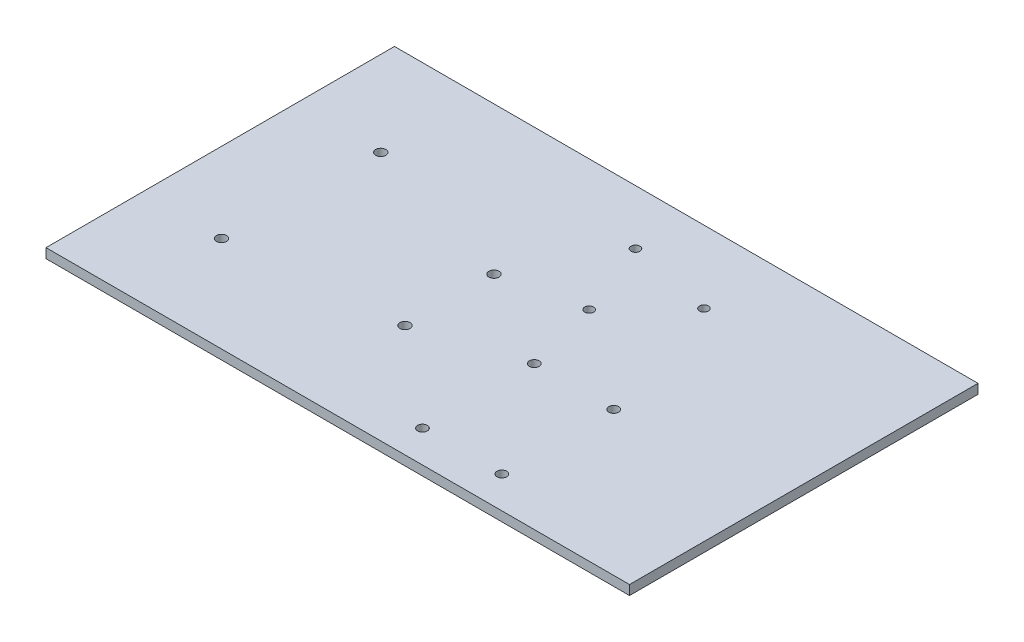
SolidWorks part; units mm, degrees
ref_plane "Front Plane" through (0, 0, 0) normal (0, 0, 1) x (1, 0, 0)
ref_plane "Top Plane" through (0, 0, 0) normal (0, 1, 0) x (1, 0, 0)
ref_plane "Right Plane" through (0, 0, 0) normal (1, 0, 0) x (0, 0, -1)
sketch "Sketch1" plane through (0, 0, 0) normal (0, 1, 0) x (1, 0, 0)
  line L1 (-91.44, 54.61) -> (91.44, 54.61)
  line L2 (-91.44, 54.61) -> (-91.44, -54.61)
  line L3 (-91.44, -54.61) -> (91.44, -54.61)
  line L4 (91.44, 54.61) -> (91.44, -54.61)
  line L5 (-91.44, 54.61) -> (91.44, -54.61) construction
  line L6 (-91.44, -54.61) -> (91.44, 54.61) construction
  point P0 (0, 0)
  dimension "D1" = 182.88
  dimension "D2" = 109.22
extrude "Boss-Extrude1" add sketch "Sketch1" along normal blind 3
sketch "Sketch2" plane through (0, 3, 0) normal (0, 1, 0) x (1, 0, 0)
  line L0 (-91.44, 54.61) -> (-91.44, -54.61) construction
  line L1 (-91.44, -54.61) -> (91.44, -54.61) construction
  line L2 (-66.44, -24.61) -> (-66.44, 28.3) construction
  line L3 (-66.44, -24.61) -> (52.1033, -24.61) construction
  circle A0 centre (-66.44, -24.61) radius 1.6
  circle A1 centre (-64.84, 23.69) radius 1.6
  circle A2 centre (-14.04, 8.39) radius 1.6
  circle A3 centre (-14.04, -19.51) radius 1.6
  dimension "D2" = 30
  dimension "D4" = 3.2
  dimension "D5" = 50.8
  dimension "D6" = 27.9
  dimension "D7" = 5.1
  dimension "D3" = 48.3
  dimension "D1" = 25
extrude "Cut-Extrude1" cut sketch "Sketch2" against normal blind 10
sketch "Sketch3" plane through (0, 3, 0) normal (0, 1, 0) x (1, 0, 0)
  line L0 (91.44, 54.61) -> (-91.44, 54.61) construction
  line L1 (91.44, -54.61) -> (91.44, 54.61) construction
  circle A0 centre (10.4954, 13.69) radius 1.4
  circle A1 centre (1.2336, 37.47) radius 1.4
  circle A2 centre (28.18, 31.98) radius 1.4
  dimension "D1" = 2.8
  dimension "D2" = 40.92
  dimension "D3" = 27.5
  dimension "D4" = 25.52
  dimension "D5" = 22.63
  dimension "D6" = 17.14
  dimension "D7" = 63.26
extrude "Cut-Extrude2" cut sketch "Sketch3" against normal through all
sketch "Sketch4" plane through (0, 3, 0) normal (0, 1, 0) x (1, 0, 0)
  line L0 (16.55, -9.56) -> (41.44, -9.56) construction
  line L1 (16.55, -9.56) -> (16.55, -44.61) construction
  line L2 (41.44, -9.56) -> (41.44, -44.61) construction
  line L3 (91.44, 54.61) -> (-91.44, 54.61) construction
  line L4 (91.44, -54.61) -> (91.44, 54.61) construction
  line L5 (-91.44, -54.61) -> (91.44, -54.61) construction
  circle A0 centre (16.55, -44.61) radius 1.525
  circle A1 centre (41.44, -9.56) radius 1.525
  circle A2 centre (16.55, -9.56) radius 1.525
  circle A3 centre (41.44, -44.61) radius 1.525
  dimension "D1" = 24.89
  dimension "D2" = 35.05
  dimension "D3" = 3.05
  dimension "D4" = 50
  dimension "D5" = 10
extrude "Cut-Extrude3" cut sketch "Sketch4" against normal through all
